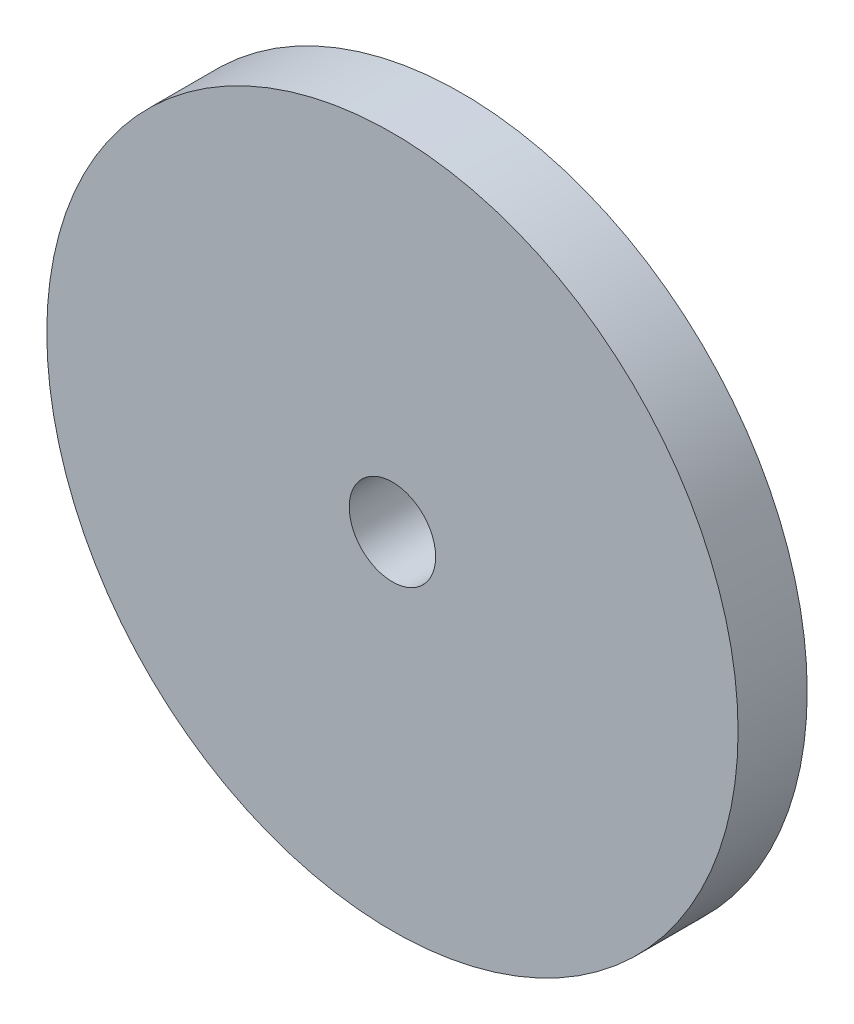
SolidWorks part; units mm, degrees
ref_plane "Plan de face" through (0, 0, 0) normal (0, 0, 1) x (1, 0, 0)
ref_plane "Plan de dessus" through (0, 0, 0) normal (0, 1, 0) x (1, 0, 0)
ref_plane "Plan de droite" through (0, 0, 0) normal (1, 0, 0) x (0, 0, -1)
sketch "Esquisse1" plane through (0, 0, 0) normal (0, 0, 1) x (1, 0, 0)
  circle A0 centre (0, 0) radius 20
  dimension "D1" = 40
extrude "Boss.-Extru.1" add sketch "Esquisse1" along normal blind 4
sketch "Esquisse2" plane through (0, 0, 4) normal (0, 0, 1) x (1, 0, 0)
  circle A0 centre (0, 0) radius 2.5
  dimension "D1" = 5
extrude "Enlèv. mat.-Extru.1" cut sketch "Esquisse2" against normal through all
